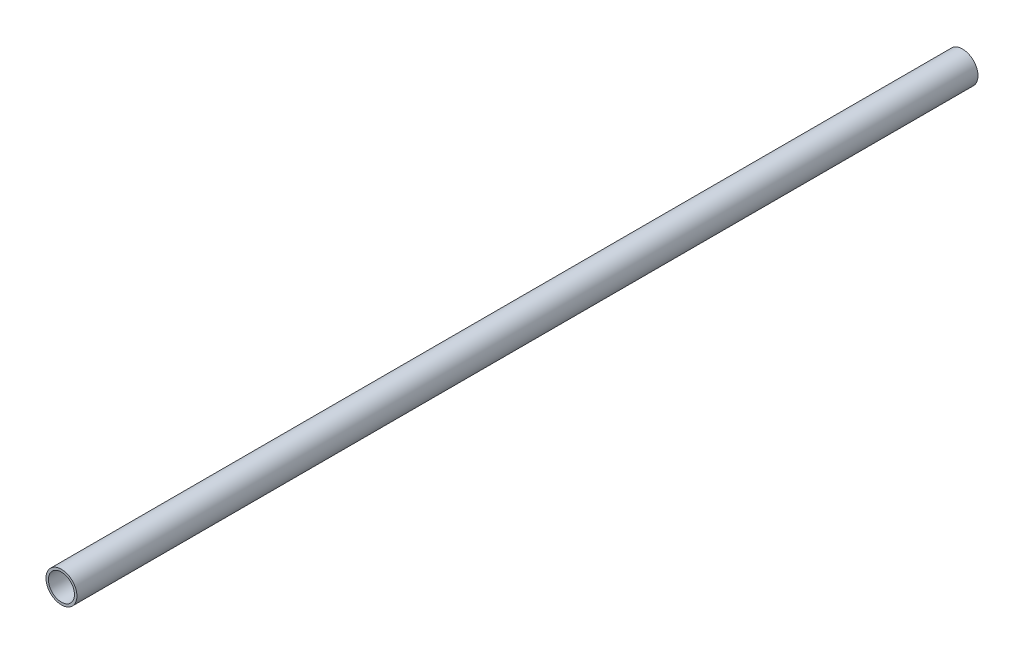
SolidWorks part; units mm, degrees
ref_plane "Alzado" through (0, 0, 0) normal (0, 0, 1) x (1, 0, 0)
ref_plane "Planta" through (0, 0, 0) normal (0, 1, 0) x (1, 0, 0)
ref_plane "Vista lateral" through (0, 0, 0) normal (1, 0, 0) x (0, 0, -1)
sketch "Croquis2" plane through (0, 0, 0) normal (0, 0, 1) x (1, 0, 0)
  circle A0 centre (0, 0) radius 6.35
  circle A1 centre (0, 0) radius 5.35
  dimension "D1" = 12.7
  dimension "D2" = 1
extrude "Saliente-Extruir1" add sketch "Croquis2" along normal blind 370
